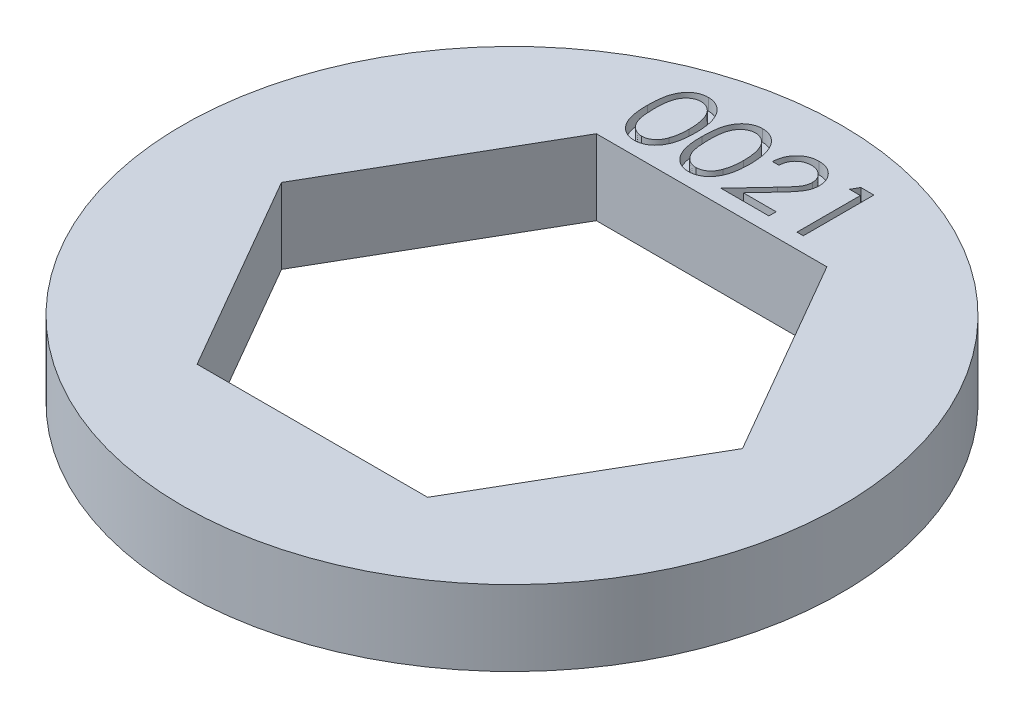
SolidWorks part; units mm, degrees
material "Nylon 101"
ref_plane "Front Plane" through (0, 0, 0) normal (0, 0, 1) x (1, 0, 0)
ref_plane "Top Plane" through (0, 0, 0) normal (0, 1, 0) x (1, 0, 0)
ref_plane "Right Plane" through (0, 0, 0) normal (1, 0, 0) x (0, 0, -1)
sketch "Sketch1" plane through (0, 0, 0) normal (0, 1, 0) x (1, 0, 0)
  line L1 (7.7723, 0) -> (3.8861, 6.731)
  line L2 (3.8861, 6.731) -> (-3.8861, 6.731)
  line L3 (-3.8861, 6.731) -> (-7.7723, 0)
  line L4 (-7.7723, 0) -> (-3.8861, -6.731)
  line L5 (-3.8861, -6.731) -> (3.8861, -6.731)
  line L6 (3.8861, -6.731) -> (7.7723, 0)
  circle A0 centre (0, 0) radius 11.1125
  circle A1 centre (0, 0) radius 6.731 construction
  dimension "D1" = 22.225
  dimension "D2" = 13.462
extrude "Boss-Extrude1" add sketch "Sketch1" along normal blind 2.54
sketch "Sketch2" plane through (0, 2.54, 0) normal (0, 1, 0) x (1, 0, 0)
  line L0 (-3.9498, 7.239) -> (2.8802, 7.239) construction
  line L1 (3.8861, 6.731) -> (-3.8861, 6.731) construction
  text T0 "0021\r\n" font "Century Gothic" height 2.3813
  point P5 (-4.9253, 5.334)
  point P6 (-5.3892, 5.334)
  point P7 (-3.9498, 7.239)
  dimension "D1" = 0.508
extrude "Cut-Extrude1" cut sketch "Sketch2" against normal blind 0.4
